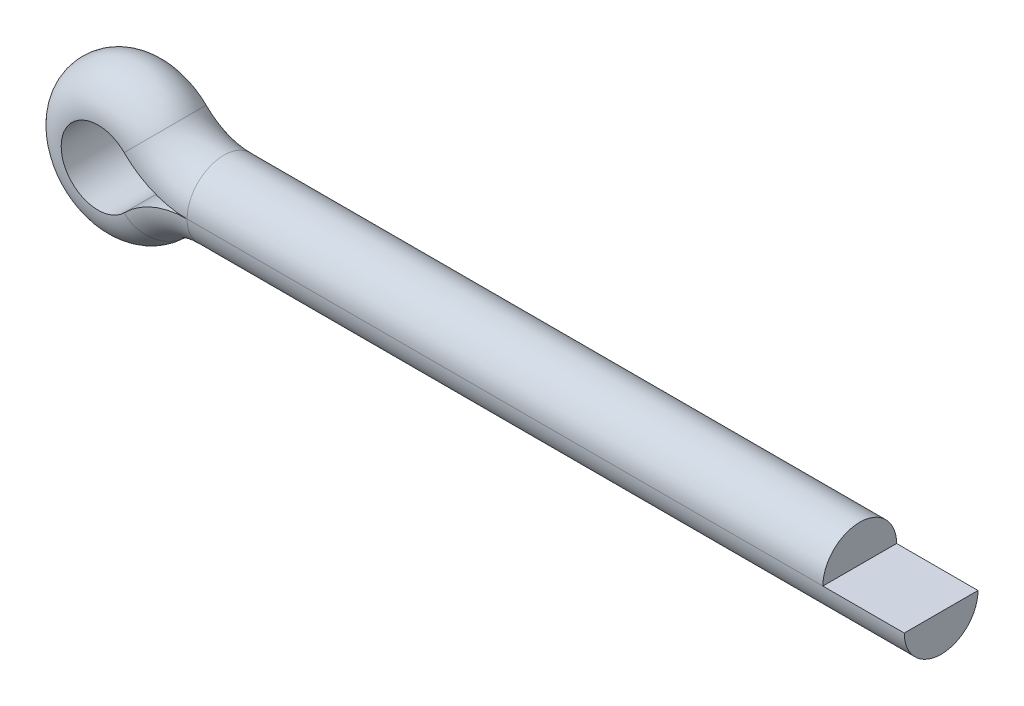
SolidWorks part; units mm, degrees
ref_plane "Front" through (0, 0, 0) normal (0, 0, 1) x (1, 0, 0)
ref_plane "Top" through (0, 0, 0) normal (0, 1, 0) x (1, 0, 0)
ref_plane "Right" through (0, 0, 0) normal (1, 0, 0) x (0, 0, -1)
other "Configuration Table"
ref_plane "Plane1" through (31.4, 0, 0) normal (1, 0, 0) x (0, 0, -1)
sketch "PathSke" plane through (1.208, 1.808, 0) normal (0, 0, 1) x (0, 1, 0)
  line L0 (-0.358, -30.192) -> (-0.358, -5.192)
  line L1 (-3.258, -5.192) -> (-3.258, -33.392)
  line L2 (-1.808, 1.208) -> (-1.808, -5.7761) construction
  arc A0 (-3.258, -5.192) -> (-3.8583, -3.7429) centre (-5.3071, -5.192) ccw
  arc A1 (-0.358, -5.192) -> (0.2424, -3.7429) centre (1.6912, -5.192) cw
  arc A3 (0.2424, -3.7429) -> (-3.8583, -3.7429) centre (-1.808, -1.692) ccw
  dimension "C" = 5.8
  dimension "d" = 2.9
  dimension "d/2" = 1.45
  dimension "l" = 25
  dimension "a" = 3.2
  dimension "b" = 6.4
sketch "SectionSke" plane through (31.4, 0.15, 0.15) normal (1, 0, 0) x (0, 1, 0)
  line L0 (-0.15, -1.6) -> (-0.15, 1.3)
  arc A0 (-0.15, -1.6) -> (-0.15, 1.3) centre (-0.15, -0.15) ccw
  dimension "R" = 1.45
  dimension "d1" = 2.9
sweep "Body" add profiles "SectionSke" path "PathSke"
equation "\"d/2@PathSke\" = \"d@PathSke\" / 2"
equation "\"R@SectionSke\" = \"d@PathSke\" / 2"
equation "\"d1@SectionSke\" = \"d@PathSke\""
equation "\"D1@Plane1\" = \"b@PathSke\" + \"l@PathSke\""
